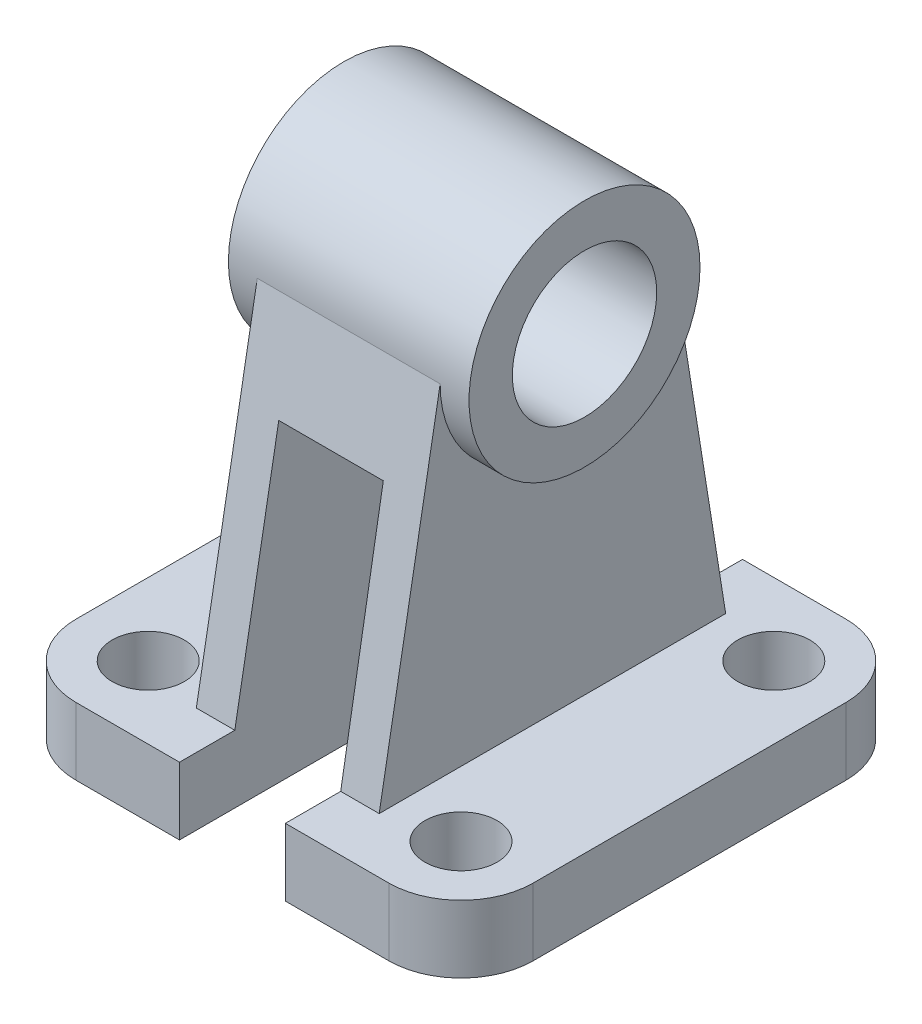
SolidWorks part; units mm, degrees
ref_plane "Front Plane" through (0, 0, 0) normal (0, 0, 1) x (1, 0, 0)
ref_plane "Top Plane" through (0, 0, 0) normal (0, 1, 0) x (1, 0, 0)
ref_plane "Right Plane" through (0, 0, 0) normal (1, 0, 0) x (0, 0, -1)
sketch "Sketch2" plane through (0, 0, 0) normal (0, 1, 0) x (1, 0, 0)
  line L1 (-9.632, 0) -> (11.868, 0)
  line L2 (-24.632, 15) -> (-24.632, 80)
  line L3 (-9.632, 95) -> (11.868, 95)
  line L4 (11.868, 0) -> (11.868, 95)
  line L5 (33.868, 0) -> (55.368, 0)
  line L6 (33.868, 0) -> (33.868, 95)
  line L7 (33.868, 95) -> (55.368, 95)
  line L8 (70.368, 15) -> (70.368, 80)
  arc A0 (-9.632, 0) -> (-24.632, 15) centre (-9.632, 15) cw
  arc A1 (55.368, 0) -> (70.368, 15) centre (55.368, 15) ccw
  arc A2 (55.368, 95) -> (70.368, 80) centre (55.368, 80) cw
  arc A3 (-24.632, 80) -> (-9.632, 95) centre (-9.632, 80) cw
  circle A4 centre (-9.632, 15) radius 7.5
  circle A5 centre (55.368, 15) radius 7.5
  circle A6 centre (-9.632, 80) radius 7.5
  circle A7 centre (55.368, 80) radius 7.5
  dimension "D2" = 15
  dimension "D3" = 15
  dimension "D4" = 15
  dimension "D5" = 15
  dimension "D1" = 22
  dimension "D6" = 21.5
  dimension "D7" = 65
  dimension "D8" = 65
extrude "Boss-Extrude2" add sketch "Sketch2" against normal blind 14
sketch "Sketch4" plane through (33.868, 0, 0) normal (-1, 0, 0) x (0, 0, 1)
  line L0 (-72.1668, 71) -> (-24.1668, 71) construction
  line L1 (-80, -14) -> (-15, -14) construction
  line L3 (-11.5, 0) -> (-24.1668, 71)
  line L4 (0, 0) -> (-15, 0) construction
  line L6 (-83.5, 0) -> (-72.1668, 71)
  line L7 (-80, 0) -> (-95, 0) construction
  line L8 (-95, 0) -> (-83.5, 0)
  line L9 (-11.5, 0) -> (0, 0)
  circle A0 centre (-48.1668, 71) radius 24
  line M4 (0, 0) -> (-95, 0)
  dimension "D2" = 48
  dimension "D1" = 85
  dimension "D3" = 11.5
  dimension "D4" = 11.5
extrude "Boss-Extrude3" add sketch "Sketch4" against normal blind 8 contours A0 L6 L3 M4 | L0 A0 | A0 L0
sketch "Sketch5" plane through (33.868, 0, 0) normal (-1, 0, 0) x (0, 0, 1)
  line L0 (-83.5, 0) -> (-11.5, 0)
  line L1 (-11.5, 0) -> (-24.1668, 71)
  line L2 (-83.5, 0) -> (-72.1668, 71)
  circle A0 centre (-48.1668, 71) radius 24
  line M7 (-11.5, 0) -> (-24.1668, 71)
  arc M8 (-24.1668, 71) -> (-72.1668, 71) centre (-48.1668, 71) ccw
  line M9 (-72.1668, 71) -> (-83.5, 0)
extrude "Boss-Extrude4" add sketch "Sketch5" along normal blind 30 contours A0 L0 M9 M7 | A0 M8
sketch "Sketch6" plane through (3.868, 0, 0) normal (-1, 0, 0) x (0, 0, 1)
  circle A0 centre (-48.1668, 71) radius 24
  circle A1 centre (-48.1668, 71) radius 15
extrude "Boss-Extrude5" add sketch "Sketch6" along normal blind 6
sketch "Sketch7" plane through (41.868, 0, 0) normal (1, 0, 0) x (0, 0, -1)
  circle A0 centre (48.1668, 71) radius 24
  circle A1 centre (48.1668, 71) radius 15
extrude "Boss-Extrude6" add sketch "Sketch7" along normal blind 6
sketch "Sketch8" plane through (41.868, 0, 0) normal (1, 0, 0) x (0, 0, -1)
  circle A0 centre (48.1668, 71) radius 15
extrude "Cut-Extrude1" cut sketch "Sketch8" against normal up to next
sketch "Sketch9" plane through (0, -1.9884, -11.1453) normal (0, 0.1756, 0.9845) x (1, 0, 0)
  line L0 (3.868, 2.0198) -> (3.868, 74.1409) construction
  line L1 (41.868, 2.0198) -> (41.868, 74.1409) construction
  line L2 (11.868, 2.0198) -> (11.868, 54.0198)
  line L3 (11.868, 54.0198) -> (33.5886, 54.0198)
  line L4 (33.5886, 54.0198) -> (33.868, 2.0198)
  line L5 (11.868, 2.0198) -> (33.868, 2.0198)
  dimension "D1" = 38
  dimension "D2" = 52
extrude "Cut-Extrude2" cut sketch "Sketch9" against normal up to next
